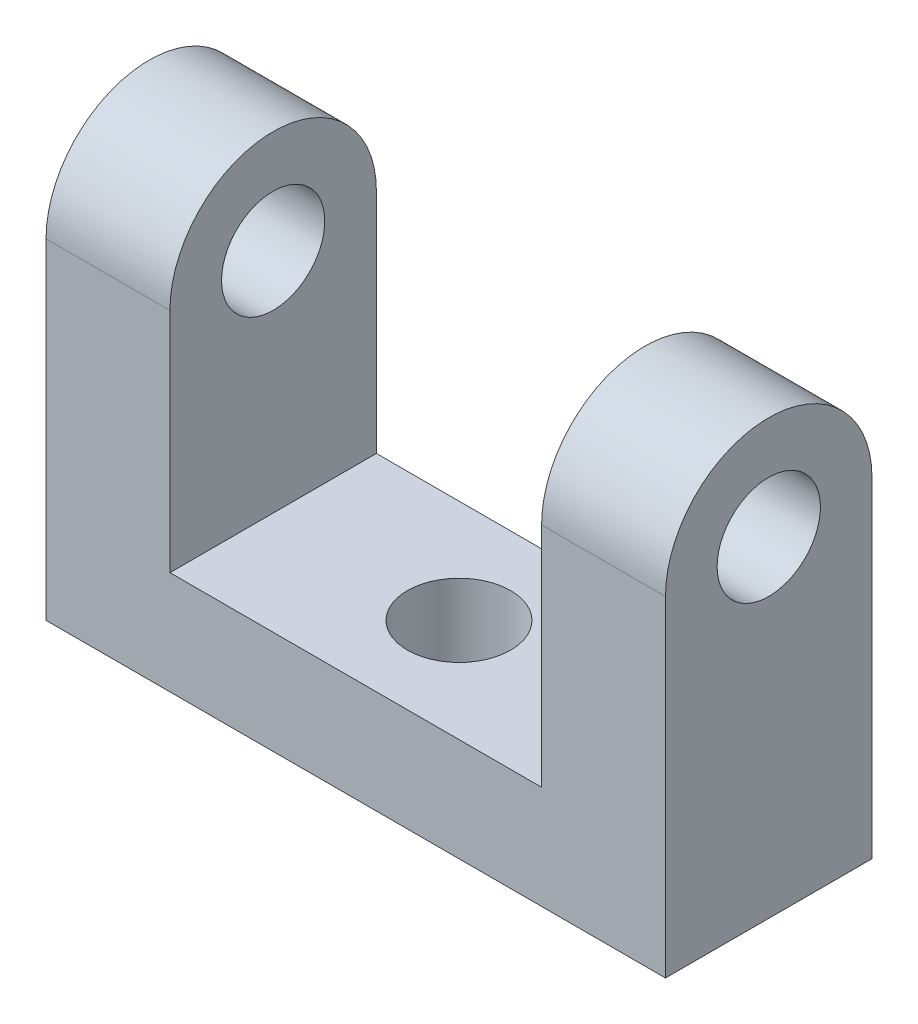
SolidWorks part; units mm, degrees
ref_plane "Front Plane" through (0, 0, 0) normal (0, 0, 1) x (1, 0, 0)
ref_plane "Top Plane" through (0, 0, 0) normal (0, 1, 0) x (1, 0, 0)
ref_plane "Right Plane" through (0, 0, 0) normal (1, 0, 0) x (0, 0, -1)
sketch "Sketch1" plane through (0, 0, 0) normal (1, 0, 0) x (0, 0, -1)
  line L0 (-6.35, 0) -> (6.35, 0)
  line L1 (6.35, 0) -> (6.35, 20.32)
  line L2 (0, 0) -> (0, 20.32) construction
  line L3 (-6.35, 0) -> (-6.35, 20.32)
  arc A0 (-6.35, 20.32) -> (6.35, 20.32) centre (0, 20.32) cw
  circle A1 centre (0, 20.32) radius 3.175
  point P4 (0, 0)
  dimension "D3" = 6.35
  dimension "D1" = 12.7
  dimension "D2" = 20.32
extrude "Boss-Extrude1" add sketch "Sketch1" along normal blind 38.1
sketch "Sketch2" plane through (0, 0, 6.35) normal (0, 0, 1) x (1, 0, 0)
  line L0 (38.1, 26.67) -> (0, 26.67) construction
  line L1 (7.62, 26.67) -> (30.48, 26.67)
  line L2 (7.62, 26.67) -> (7.62, 6.35)
  line L3 (7.62, 6.35) -> (30.48, 6.35)
  line L4 (30.48, 26.67) -> (30.48, 6.35)
  line L5 (19.05, 6.35) -> (19.05, 0) construction
  line L6 (38.1, 0) -> (0, 0) construction
  dimension "D1" = 22.86
  dimension "D2" = 20.32
extrude "Cut-Extrude1" cut sketch "Sketch2" against normal blind 25.4
sketch "Sketch3" plane through (0, 6.35, 0) normal (0, 1, 0) x (1, 0, 0)
  line L0 (19.05, 0) -> (19.05, 6.35) construction
  line L1 (7.62, 6.35) -> (30.48, 6.35) construction
  line L2 (19.05, 0) -> (0, 0) construction
  line L3 (0, 6.35) -> (0, -6.35) construction
  circle A0 centre (19.05, 0) radius 3.175
  dimension "D1" = 6.35
extrude "Cut-Extrude2" cut sketch "Sketch3" against normal blind 25.4
